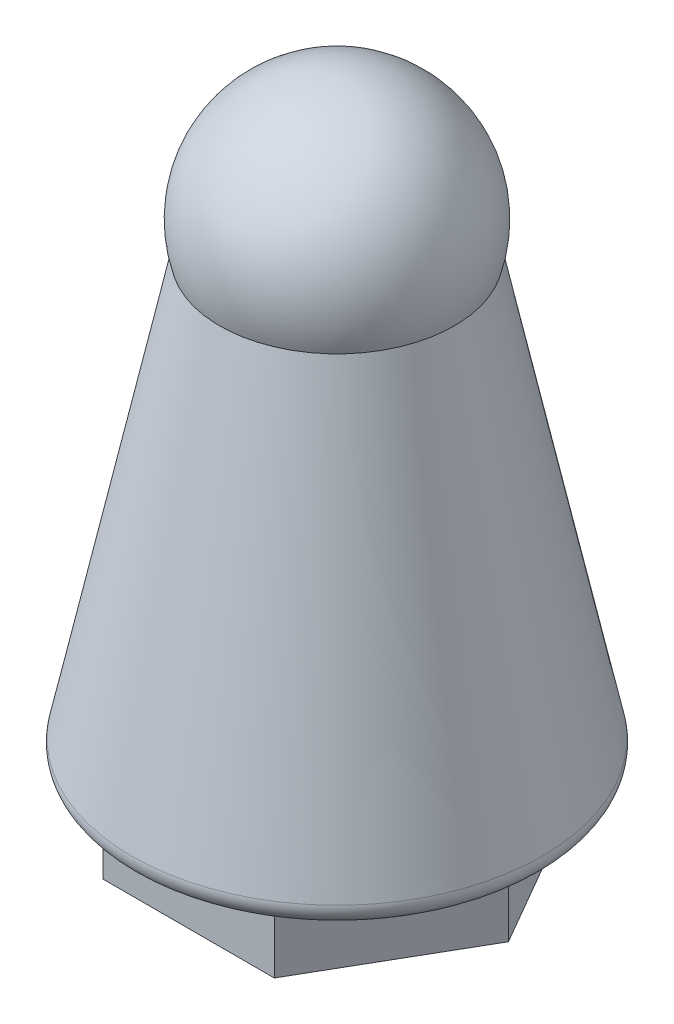
SolidWorks part; units mm, degrees
ref_plane "Front Plane" through (0, 0, 0) normal (0, 0, 1) x (1, 0, 0)
ref_plane "Top Plane" through (0, 0, 0) normal (0, 1, 0) x (1, 0, 0)
ref_plane "Right Plane" through (0, 0, 0) normal (1, 0, 0) x (0, 0, -1)
sketch "Sketch1" plane through (0, 0, 0) normal (0, 0, 1) x (1, 0, 0)
  line L0 (0, 0) -> (0, 77.9501) construction
  line L1 (-6.7243, 69.0051) -> (-12, 44.0051)
  line L2 (-12, 44.0051) -> (0, 44.0051)
  line L3 (0, 77.9501) -> (0, 44.0051)
  arc A0 (0, 77.9501) -> (-6.7243, 69.0051) centre (0, 70.9501) ccw
  dimension "D1" = 25
  dimension "D3" = 7
  dimension "D2" = 12
revolve "Revolve1" add sketch "Sketch1" angle 360 about L0
ref_plane "Plane1" through (0, 40.0051, 0) normal (0, -1, 0) x (-1, 0, 0)
sketch "Sketch2" plane through (0, 40.0051, 0) normal (0, -1, 0) x (1, 0, 0)
  line L0 (55, 0) -> (-55, 0) construction
  line L1 (9.815, 0) -> (4.9075, 8.5)
  line L2 (4.9075, 8.5) -> (-4.9075, 8.5)
  line L3 (-4.9075, 8.5) -> (-9.815, 0)
  line L4 (-9.815, 0) -> (-4.9075, -8.5)
  line L5 (-4.9075, -8.5) -> (4.9075, -8.5)
  line L6 (4.9075, -8.5) -> (9.815, 0)
  circle A0 centre (0, 0) radius 8.5 construction
  circle A1 centre (0, 0) radius 5
  point P1 (0, 0)
  dimension "D2" = 10
  dimension "D1" = 17
extrude "Boss-Extrude1" add sketch "Sketch2" against normal blind 8
fillet "Fillet1" radius 1 1 edges at (0, 44.0051, -12)
